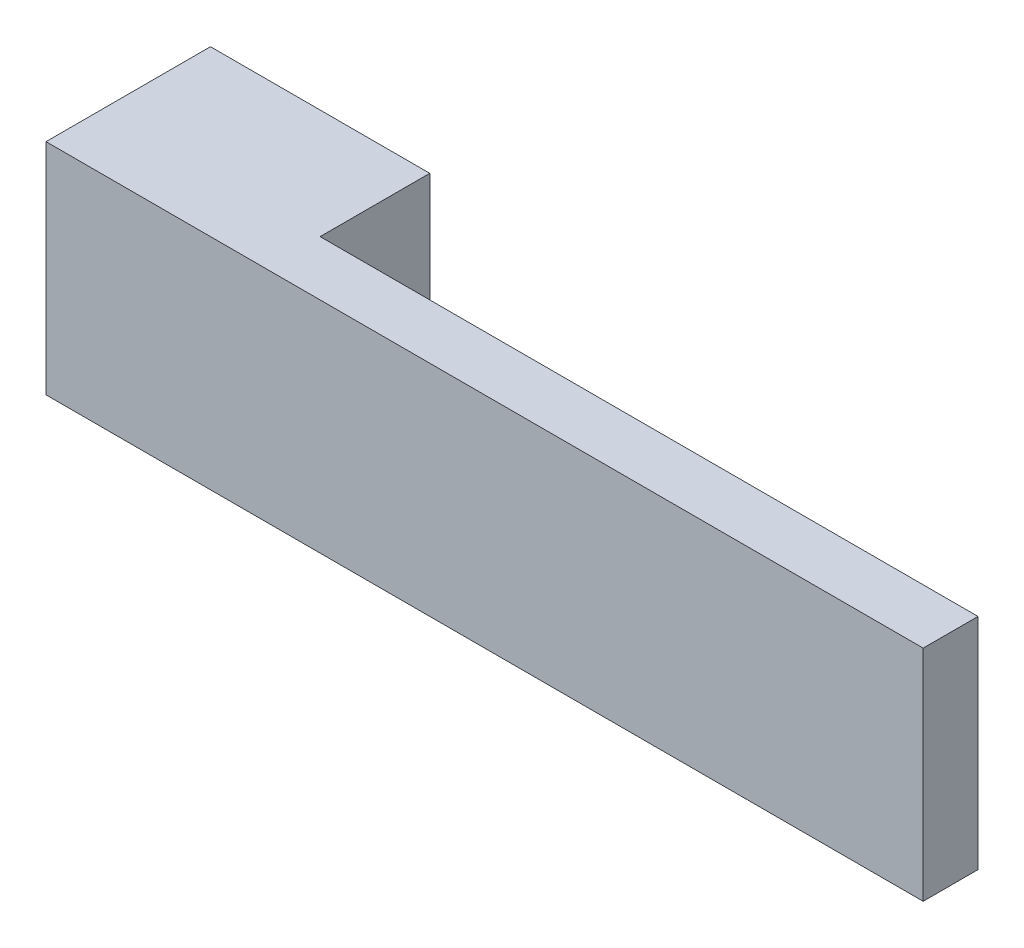
SolidWorks part; units mm, degrees
ref_plane "Přední rovina" through (0, 0, 0) normal (0, 0, 1) x (1, 0, 0)
ref_plane "Horní rovina" through (0, 0, 0) normal (0, 1, 0) x (1, 0, 0)
ref_plane "Pravá rovina" through (0, 0, 0) normal (1, 0, 0) x (0, 0, -1)
sketch "Sketch2" plane through (0, 0, 0) normal (0, 1, 0) x (1, 0, 0)
  line L0 (0, -15) -> (0, 0)
  line L1 (80, -15) -> (0, -15)
  line L2 (80, -15) -> (80, -10)
  line L3 (80, -10) -> (20, -10)
  line L7 (0, 0) -> (20, 0)
  line L8 (20, -10) -> (20, 0)
  dimension "D1" = 80
  dimension "D2" = 5
  dimension "D3" = 10
  dimension "D4" = 20
extrude "Boss-Extrude1" add sketch "Sketch2" along normal blind 20
